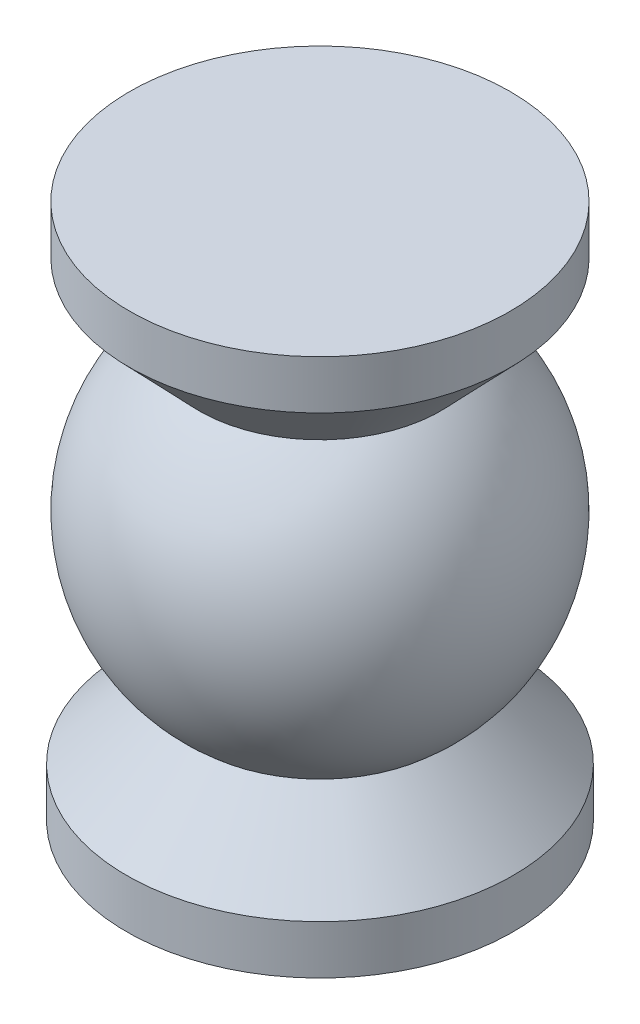
SolidWorks part; units mm, degrees
ref_plane "前视基准面" through (0, 0, 0) normal (0, 0, 1) x (1, 0, 0)
ref_plane "上视基准面" through (0, 0, 0) normal (0, 1, 0) x (1, 0, 0)
ref_plane "右视基准面" through (0, 0, 0) normal (1, 0, 0) x (0, 0, -1)
other "Configuration Table"
sketch "草图1" plane through (0, 0, 0) normal (0, 0, 1) x (1, 0, 0)
  line L0 (-1, -999.2) -> (-1, 49000.8) construction
  line L6 (-15.4, 20) -> (-25, 30.0017)
  line L14 (-25, 30.0017) -> (-25, 35.0017)
  line L15 (-25, 35.0017) -> (-1, 35.0017)
  line L17 (-15.4, -18.4) -> (-25.4, -28.4017)
  line L19 (-25.4, -33.4017) -> (-1, -33.4017)
  line L20 (-25.4, -28.4017) -> (-25.4, -33.4017)
  arc A1 (-15.4, 20) -> (-15.4, -18.4) centre (-1, 0.8) ccw
  point P10 (0, 0)
  point P13 (0, -20)
  point P16 (0, 20)
  dimension "D2" = 24
revolve "旋转-薄壁3" add sketch "草图1" angle 360 about L0 wall 1
sketch "草图2" plane through (0, 36.0017, 0) normal (0, 1, 0) x (1, 0, 0)
  circle A1 centre (-1, 0) radius 25
  circle A2 centre (-1, 0) radius 25
  dimension "D1" = 0
sketch "草图3" plane through (0, 36.0017, 0) normal (0, 1, 0) x (1, 0, 0)
  circle A0 centre (-1, 0) radius 1.5
  dimension "D1" = 3
